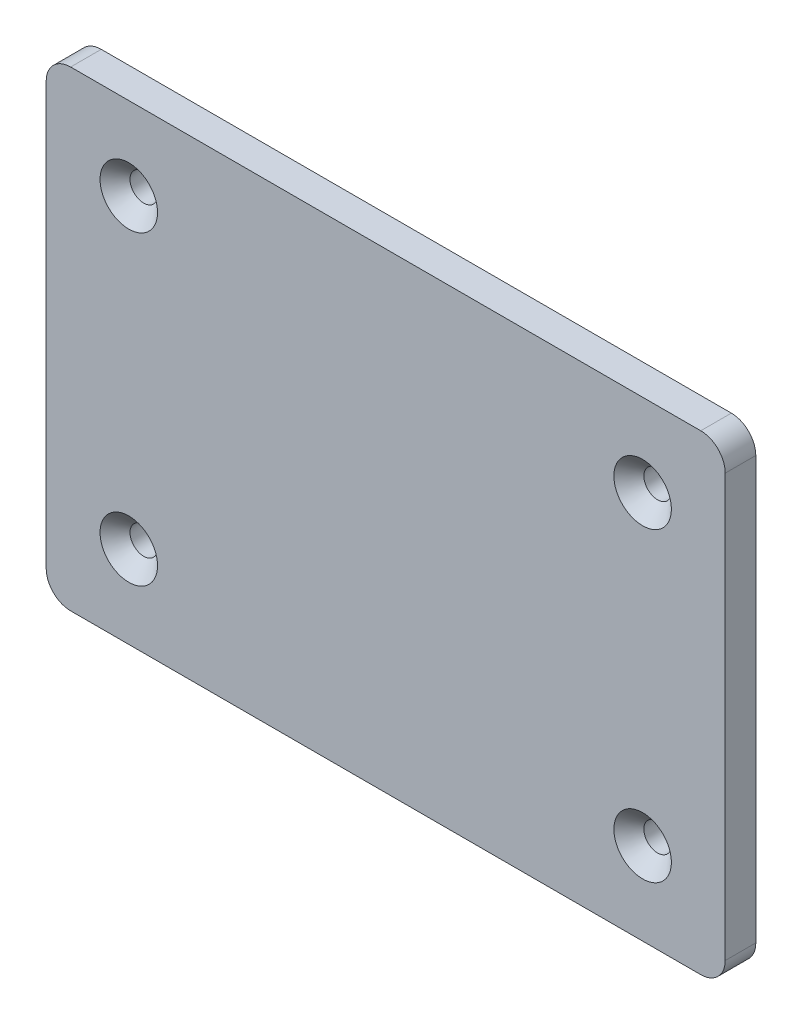
SolidWorks part; units mm, degrees
material "3.1325 (EN-AW 2017A)"
ref_plane "Front Plane" through (0, 0, 0) normal (0, 0, 1) x (1, 0, 0)
ref_plane "Top Plane" through (0, 0, 0) normal (0, 1, 0) x (1, 0, 0)
ref_plane "Right Plane" through (0, 0, 0) normal (1, 0, 0) x (0, 0, -1)
sketch "ｽｹｯﾁ1" plane through (0, 0, 0) normal (0, 0, 1) x (1, 0, 0)
  line L0 (-37.5, -6) -> (0, -6) construction
  line L1 (-37.5, 16) -> (-37.5, -28) construction
  line L2 (0, -6) -> (0, 36.722) construction
  line L3 (-54, -43) -> (-54, 31) construction
  line L4 (-47, -36) -> (47, -36) construction
  line L5 (-47, -36) -> (-47, 24) construction
  line L6 (-47, 24) -> (47, 24) construction
  line L7 (47, -36) -> (47, 24) construction
  line L8 (-47, -36) -> (47, 24) construction
  line L9 (-47, 24) -> (47, -36) construction
  line L10 (-54, 31) -> (54, 31) construction
  line L11 (54, -43) -> (54, 31) construction
  line L12 (-54, -43) -> (54, -43) construction
  line L13 (-55.5, -44.5) -> (-55.5, 32.5)
  line L14 (-55.5, 32.5) -> (55.5, 32.5)
  line L15 (55.5, -44.5) -> (55.5, 32.5)
  line L16 (-55.5, -44.5) -> (55.5, -44.5)
  circle A0 centre (-42, 19) radius 2
  circle A2 centre (42, 19) radius 2
  circle A3 centre (42, -31) radius 2
  circle A4 centre (-42, -31) radius 2
  circle A5 centre (-42, 19) radius 5 construction
  dimension "D1" = 4
  dimension "D2" = 10
  dimension "D3" = 7
  dimension "D4" = 1.5
extrude "ﾎﾞｽ - 押し出し1" add sketch "ｽｹｯﾁ1" along normal blind 5
sketch "ｽｹｯﾁ2" plane through (0, 0, 0) normal (0, 0, -1) x (-1, 0, 0)
  line L0 (47, -36) -> (47, 24) construction
  line L1 (54, -43) -> (54, 31) construction
  line L2 (54, -43) -> (-54, -43) construction
  line L3 (47, -36) -> (-47, -36) construction
  line L4 (-47, -36) -> (-47, 24) construction
  line L5 (-54, -43) -> (-54, 31) construction
  line L6 (47, 24) -> (-47, 24) construction
  line L7 (54, 31) -> (-54, 31) construction
  line L8 (47, -36) -> (47, 24)
  line L9 (54, -43) -> (54, 31)
  line L10 (54, -43) -> (-54, -43)
  line L11 (47, -36) -> (-47, -36)
  line L12 (-47, -36) -> (-47, 24)
  line L13 (-54, -43) -> (-54, 31)
  line L14 (47, 24) -> (-47, 24)
  line L15 (54, 31) -> (-54, 31)
extrude "ｶｯﾄ - 押し出し1" cut sketch "ｽｹｯﾁ2" against normal blind 4.5
sketch "ｽｹｯﾁ3" plane through (0, 0, 0) normal (0, 0, -1) x (-1, 0, 0)
  line L0 (13.5722, -6) -> (0, -6) construction
  line L1 (-37, -31) -> (37, -31)
  line L2 (-42, -26) -> (-42, 14)
  line L3 (-37, 19) -> (37, 19)
  line L4 (42, -26) -> (42, 14)
  line L5 (-42, -31) -> (42, 19) construction
  line L6 (-42, 19) -> (42, -31) construction
  line L7 (37.5, -6) -> (0, -6) construction
  line L8 (0, -6) -> (0, 10.3389) construction
  line L9 (0, -6) -> (0, 36.722) construction
  circle A0 centre (42, 19) radius 5 construction
  arc A1 (37, 19) -> (42, 14) centre (42, 19) ccw
  arc A2 (37, -31) -> (42, -26) centre (42, -31) cw
  arc A3 (-37, -31) -> (-42, -26) centre (-42, -31) ccw
  arc A4 (-37, 19) -> (-42, 14) centre (-42, 19) cw
  point P0 (0, -6)
extrude "ｶｯﾄ - 押し出し2" cut sketch "ｽｹｯﾁ3" against normal blind 4
fillet "ﾌｨﾚｯﾄ1" radius 4 20 edges at (-47, 24, 2.25) (-47, -36, 2.25) (37, 19, 2) (42, 14, 2) (42, -26, 2) (37, -31, 2) (-37, -31, 2) (-42, -26, 2) (-42, 14, 2) (-37, 19, 2) (47, -36, 2.25) (55.5, -44.5, 2.5) (55.5, 32.5, 2.5) (-55.5, 32.5, 2.5) (-55.5, -44.5, 2.5) (-54, 31, 2.25) (54, -43, 2.25) (-54, -43, 2.25) (54, 31, 2.25) (47, 24, 2.25)
hole_wizard "M4 丸皿ねじ用皿穴1" positions "ｽｹｯﾁ4" profile "ｽｹｯﾁ5" countersink size "M4" standard "JIS" end condition through all
sketch "ｽｹｯﾁ4" plane through (0, 0, 5) normal (0, 0, 1) x (1, 0, 0)
  point P0 (-42, 19)
  point P3 (-42, -31)
  point P6 (42, -31)
  point P9 (42, 19)
sketch "ｽｹｯﾁ5" plane through (-42, 19, 5) normal (1, 0, 0) x (0, -1, 0)
  line L0 (0, 0) -> (0, 5)
  line L1 (0, 5) -> (2.25, 5)
  line L2 (2.25, 5) -> (2.25, 2.45)
  line L3 (2.25, 2.45) -> (4.7, 0)
  line L5 (4.7, 0) -> (0, 0)
  line L6 (-2.25, 2.45) -> (-4.7, 0) construction
  line L11 (0, -6.35) -> (0, 107.95) construction
  dimension "通し穴の直径" = 4.5
  dimension "通し穴の深さ" = 5
  dimension "表面の皿穴の直径" = 9.4
  dimension "表面の皿穴の角度" = 90
